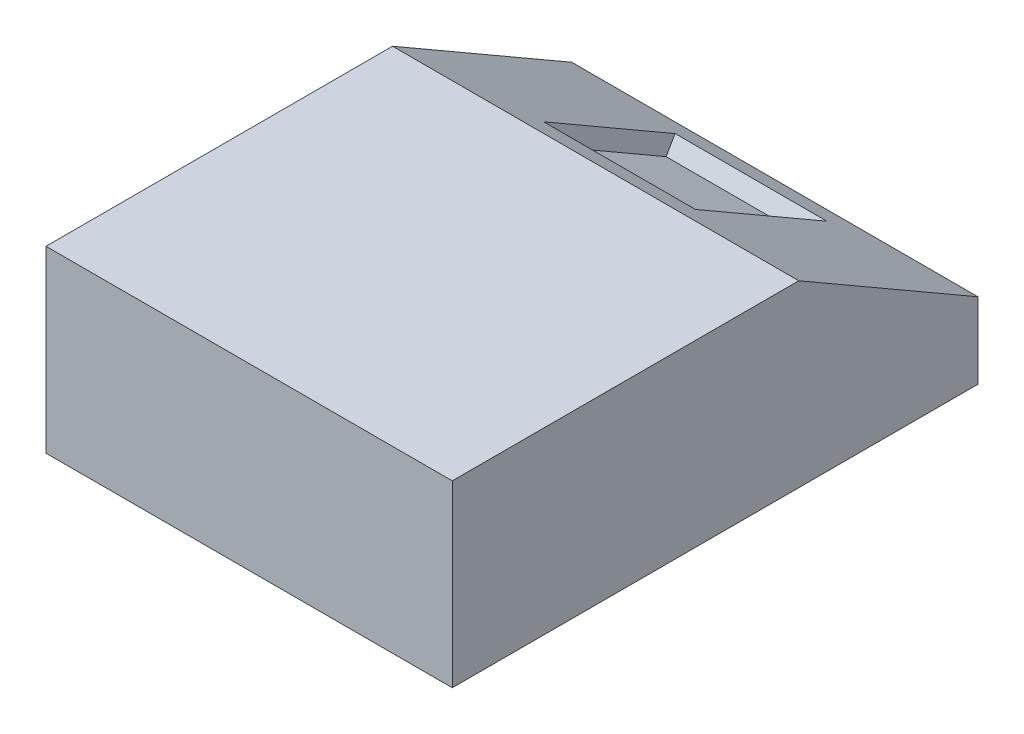
SolidWorks part; units mm, degrees
ref_plane "Front Plane" through (0, 0, 0) normal (0, 0, 1) x (1, 0, 0)
ref_plane "Top Plane" through (0, 0, 0) normal (0, 1, 0) x (1, 0, 0)
ref_plane "Right Plane" through (0, 0, 0) normal (1, 0, 0) x (0, 0, -1)
sketch "Sketch2" plane through (0, 0, 0) normal (0, 1, 0) x (1, 0, 0)
  line L1 (-31, 41) -> (31, 41)
  line L2 (-31, 41) -> (-31, -41)
  line L3 (-31, -41) -> (31, -41)
  line L4 (31, 41) -> (31, -41)
  line L5 (-31, 41) -> (31, -41) construction
  line L6 (-31, -41) -> (31, 41) construction
  line L7 (-34, 44) -> (34, 44)
  line L8 (-34, 44) -> (-34, -44)
  line L9 (-34, -44) -> (34, -44)
  line L10 (34, 44) -> (34, -44)
  line L11 (-34, 44) -> (34, -44) construction
  line L12 (-34, -44) -> (34, 44) construction
  point P0 (0, 0)
  point P6 (0, 0)
  dimension "D1" = 82
  dimension "D2" = 62
  dimension "D3" = 3
  dimension "D4" = 3
extrude "Boss-Extrude1" add sketch "Sketch2" along normal blind 30 contours L10 L7 L8 L9 L1 L4 L3 L2 | L4 L1 L2 L3
chamfer "Chamfer1" distance 30 angle 30 1 edges at (0, 30, -44)
shell "Shell1" thickness 3
sketch "Sketch3" plane through (0, 28.5622, -16.4904) normal (0, 0.866, -0.5) x (1, 0, 0)
  line L0 (0, 31.7654) -> (0, -2.8756) construction
  line L1 (-12.7, 27.1449) -> (12.7, 27.1449)
  line L2 (-12.7, 27.1449) -> (-12.7, 1.7449)
  line L3 (-12.7, 1.7449) -> (12.7, 1.7449)
  line L4 (12.7, 27.1449) -> (12.7, 1.7449)
  line L5 (-12.7, 27.1449) -> (12.7, 1.7449) construction
  line L6 (-12.7, 1.7449) -> (12.7, 27.1449) construction
  line L7 (-34, 31.7654) -> (34, 31.7654) construction
  line L8 (34, -2.8756) -> (-34, -2.8756) construction
  point P0 (0, 14.4449)
  point P11 (0, 14.4449)
  dimension "D1" = 25.4
  dimension "D2" = 25.4
extrude "Cut-Extrude1" cut sketch "Sketch3" against normal up to next
